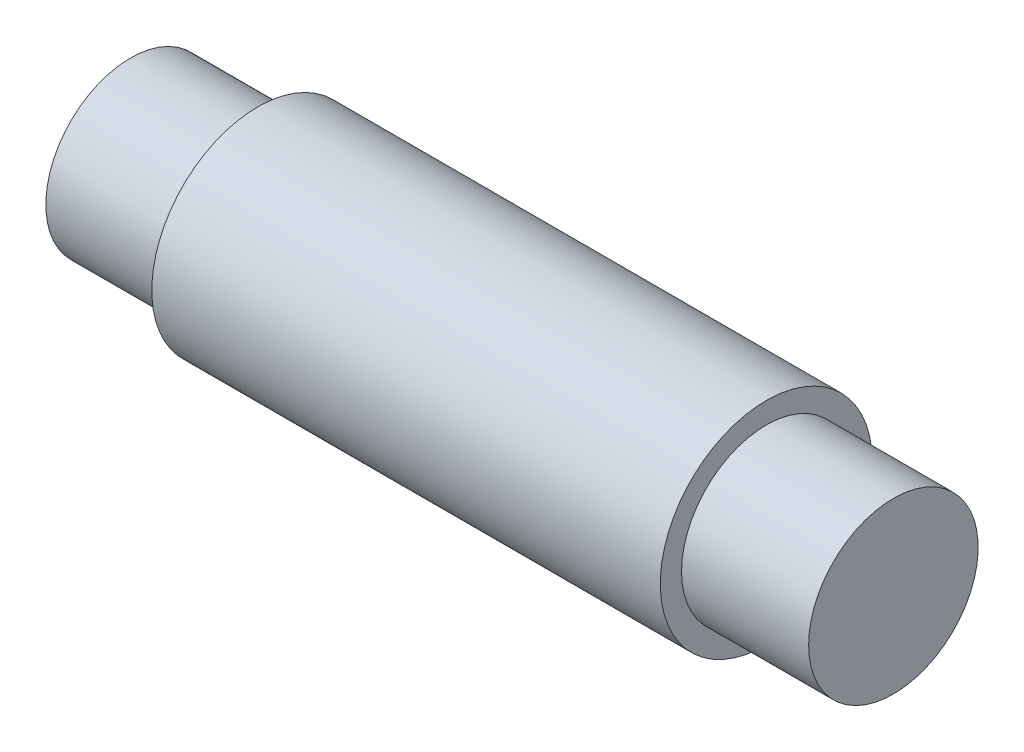
SolidWorks part; units mm, degrees
ref_plane "Front Plane" through (0, 0, 0) normal (0, 0, 1) x (1, 0, 0)
ref_plane "Top Plane" through (0, 0, 0) normal (0, 1, 0) x (1, 0, 0)
ref_plane "Right Plane" through (0, 0, 0) normal (1, 0, 0) x (0, 0, -1)
sketch "Sketch2" plane through (0, 0, 0) normal (1, 0, 0) x (0, 0, -1)
  circle A0 centre (0, 0) radius 3.175
  dimension "D1" = 6.35
extrude "Boss-Extrude1" add sketch "Sketch2" along normal mid plane 4.7625
sketch "Sketch3" plane through (-2.3813, 0, 0) normal (-1, 0, 0) x (0, 0, 1)
  circle A0 centre (0, 0) radius 3.9688
  dimension "D1" = 7.9375
extrude "Boss-Extrude2" add sketch "Sketch3" along normal blind 19.05
sketch "Sketch5" plane through (-21.4313, 0, 0) normal (-1, 0, 0) x (0, 0, 1)
  circle A0 centre (0, 0) radius 3.175
  dimension "D1" = 6.35
extrude "Boss-Extrude3" add sketch "Sketch5" along normal blind 4.7625
